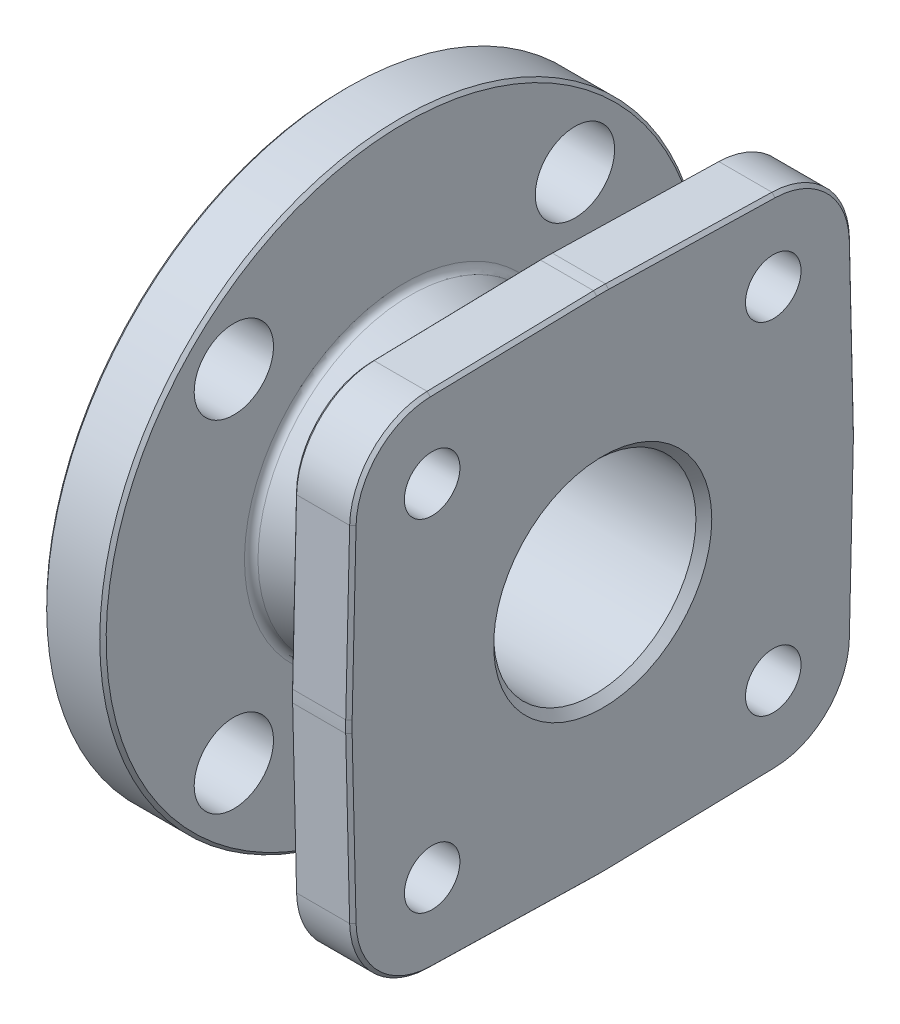
SolidWorks part; units mm, degrees
ref_plane "Front Plane" through (0, 0, 0) normal (0, 0, 1) x (1, 0, 0)
ref_plane "Top Plane" through (0, 0, 0) normal (0, 1, 0) x (1, 0, 0)
ref_plane "Right Plane" through (0, 0, 0) normal (1, 0, 0) x (0, 0, -1)
sketch "Sketch1" plane through (0, 0, 0) normal (1, 0, 0) x (0, 0, -1)
  line L0 (28.7057, 0) -> (0, 0) construction
  line L1 (0, 0) -> (0, -31.0332) construction
  line L2 (-62.9945, 43.4707) -> (-63.9823, 1.5061)
  line L3 (-43.4707, 62.9945) -> (-1.5061, 63.9823)
  line L4 (43.4707, 62.9945) -> (1.5061, 63.9823)
  line L5 (62.9945, 43.4707) -> (63.9823, 1.5061)
  line L6 (43.4707, -62.9945) -> (1.5061, -63.9823)
  line L7 (-43.4707, -62.9945) -> (-1.5061, -63.9823)
  line L8 (-62.9945, -43.4707) -> (-63.9823, -1.5061)
  line L9 (62.9945, -43.4707) -> (63.9823, -1.5061)
  arc A0 (-63.9823, 1.5061) -> (-63.9823, -1.5061) centre (0, 0) ccw
  arc A1 (-43.4707, 62.9945) -> (-62.9945, 43.4707) centre (-43, 43) ccw
  arc A2 (43.4707, 62.9945) -> (62.9945, 43.4707) centre (43, 43) cw
  arc A3 (43.4707, -62.9945) -> (62.9945, -43.4707) centre (43, -43) ccw
  arc A4 (-43.4707, -62.9945) -> (-62.9945, -43.4707) centre (-43, -43) cw
  arc A5 (1.5061, 63.9823) -> (-1.5061, 63.9823) centre (0, 0) ccw
  arc A6 (63.9823, -1.5061) -> (63.9823, 1.5061) centre (0, 0) ccw
  arc A7 (-1.5061, -63.9823) -> (1.5061, -63.9823) centre (0, 0) ccw
  dimension "D1" = 128
  dimension "D2" = 40
  dimension "D3" = 43
  dimension "D4" = 43
extrude "Boss-Extrude1" add sketch "Sketch1" against normal blind 15
sketch "Sketch2" plane through (0, 0, 0) normal (0, 0, 1) x (1, 0, 0)
  line L0 (-15, 47.5) -> (-17, 45.5)
  line L3 (-17, 45.5) -> (-17, 34.5)
  line L4 (-17, 34.5) -> (-34, 34.5)
  line L5 (-34, 34.5) -> (-50, 38.7872)
  line L6 (-50, 38.7872) -> (-50, 76)
  line L7 (-50, 76) -> (-65, 76)
  line L8 (-65, 76) -> (-65, 48)
  line L9 (-65, 48) -> (-67, 46)
  line L10 (-67, 46) -> (-67, 0)
  line L11 (-67, 0) -> (-15, 0)
  line L12 (-15, 1.5061) -> (-15, -1.5061) construction
  line L13 (-15, 0) -> (-15, 47.5)
  line L14 (-15, 62.9945) -> (-15, 43.4707) construction
  line L15 (0, 1.5061) -> (0, 43.4707) construction
  point P4 (-112.2409, 45.5507)
  point P16 (-109.9156, 48.8123)
  dimension "D1" = 34.5
  dimension "D2" = 45
  dimension "D3" = 2
  dimension "D4" = 47.5
  dimension "D5" = 15
  dimension "D6" = 2
  dimension "D7" = 15
  dimension "D8" = 46
  dimension "D9" = 76
  dimension "D10" = 34
  dimension "D11" = 67
revolve "Revolve1" add sketch "Sketch2" angle 360 about L11
hole_wizard "Hole1" positions "Sketch3" profile "Sketch4" legacy end condition through all
sketch "Sketch3" plane through (-67, 0, 0) normal (-1, 0, 0) x (0, 0, 1)
  point P0 (0, 0)
sketch "Sketch4" plane through (-67, 0, 0) normal (0, 1, 0) x (0, 0, 1)
  line L0 (0, 0) -> (0, 67)
  line L1 (0, 67) -> (25.5, 67)
  line L2 (25.5, 67) -> (25.5, 0)
  line L3 (25.5, 0) -> (0, 0)
  line L4 (0, 110) -> (0, -10) construction
  dimension "Diameter" = 51
  dimension "Depth" = 67
hole_wizard "Hole2" positions "Sketch5" profile "Sketch6" legacy
sketch "Sketch5" plane through (0, 0, 0) normal (1, 0, 0) x (0, 0, -1)
  point P0 (43, 43)
  point P3 (43, -43)
  point P6 (-43, -43)
  point P9 (-43, 43)
sketch "Sketch6" plane through (0, 43, -43) normal (0, 1, 0) x (0, 0, -1)
  line L0 (0, 0) -> (0, 15)
  line L1 (0, 15) -> (7, 15)
  line L2 (7, 15) -> (7, 0)
  line L3 (7, 0) -> (0, 0)
  line L4 (0, 110) -> (0, -10) construction
  dimension "Diameter" = 14
  dimension "Depth" = 15
hole_wizard "Hole3" positions "Sketch7" profile "Sketch8" legacy
sketch "Sketch7" plane through (-65, 0, 0) normal (-1, 0, 0) x (0, 0, 1)
  point P0 (43, 43)
  point P3 (-43, 43)
  point P6 (-43, -43)
  point P9 (43, -43)
sketch "Sketch8" plane through (-65, 43, 43) normal (0, 1, 0) x (0, 0, 1)
  line L0 (0, 0) -> (0, 15)
  line L1 (0, 15) -> (10, 15)
  line L2 (10, 15) -> (10, 0)
  line L3 (10, 0) -> (0, 0)
  line L4 (0, 110) -> (0, -10) construction
  dimension "Diameter" = 20
  dimension "Depth" = 15
fillet "Fillet1" radius 2 2 edges at (-17, -34.5, 0) (-50, -38.7872, 0)
chamfer "Chamfer1" distance 0.81 angle 45 34 edges at (-65, -76, 0) (-50, -76, 0) (-15, -57.1421, 57.1421) (-15, -63.4884, 22.4884) (-15, -22.4884, 63.4884) (-15, -64, 0) (-15, 0, 64) (-15, -63.4884, -22.4884) (-15, 22.4884, 63.4884) (-15, -57.1421, -57.1421) (-15, 57.1421, 57.1421) (-15, -22.4884, -63.4884) (-15, 63.4884, 22.4884) (-15, 0, -64) (-15, 64, 0) (-15, 22.4884, -63.4884) (-15, 63.4884, -22.4884) (-15, 57.1421, -57.1421) (0, -57.1421, -57.1421) (0, -22.4884, -63.4884) (0, -63.4884, -22.4884) (0, 0, -64) (0, -64, 0) (0, 22.4884, -63.4884) (0, -63.4884, 22.4884) (0, 57.1421, -57.1421) (0, -57.1421, 57.1421) (0, 63.4884, -22.4884) (0, -22.4884, 63.4884) (0, 64, 0) (0, 0, 64) (0, 63.4884, 22.4884) (0, 22.4884, 63.4884) (0, 57.1421, 57.1421)
chamfer "Chamfer2" distance 2 angle 45 2 edges at (-67, 0, 25.5) (0, 0, 25.5)
